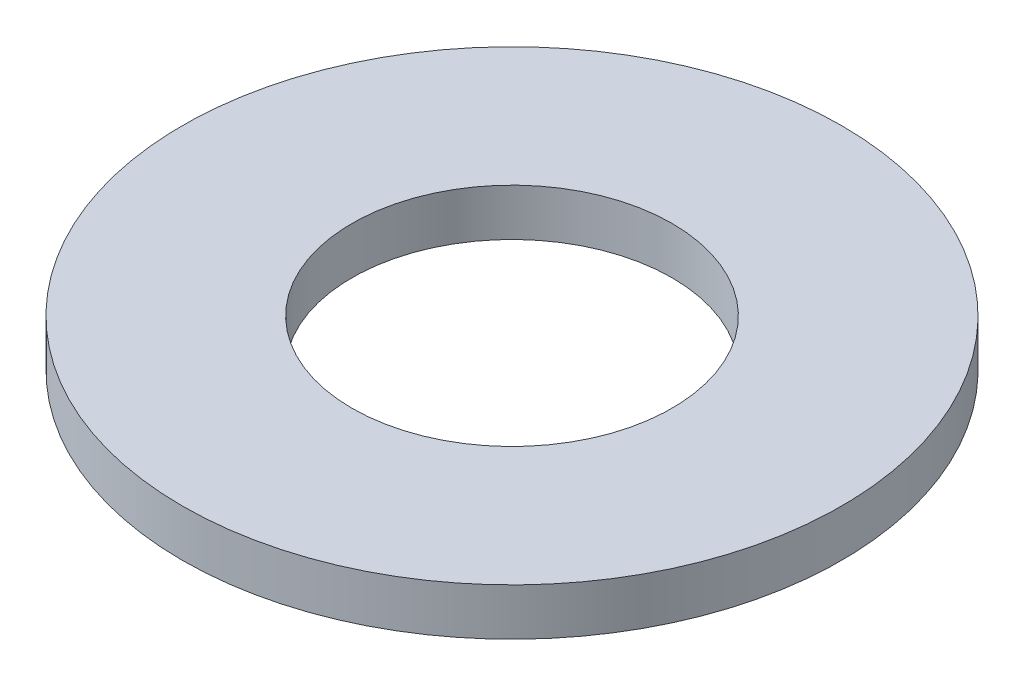
SolidWorks part; units mm, degrees
ref_plane "基准面1" through (0, 0, 0) normal (0, 0, 1) x (1, 0, 0)
ref_plane "基准面2" through (0, 0, 0) normal (0, 1, 0) x (1, 0, 0)
ref_plane "基准面3" through (0, 0, 0) normal (1, 0, 0) x (0, 0, -1)
sketch "尺寸草图" plane through (0, 0, 0) normal (0, 0, 1) x (1, 0, 0)
  line L0 (0, 0) -> (7, 0) construction
  point P3 (0.5, 0)
  point P4 (7, 0)
  point P5 (3.4, 0)
  dimension "h" = 0.5
  dimension "d2" = 7
  dimension "d1" = 3.4
sketch "草图1" plane through (0, 0, 0) normal (0, 0, 1) x (1, 0, 0)
  line L0 (0, 0) -> (0, 52.7318) construction
  line L2 (-1.7, 8.6445) -> (-3.5, 8.6445)
  line L3 (-1.7, 8.6445) -> (-1.7, 9.1445)
  line L4 (-1.7, 9.1445) -> (-3.5, 9.1445)
  line L5 (-3.5, 8.6445) -> (-3.5, 9.1445)
  dimension "D1" = 1.7
  dimension "D2" = 3.5
  dimension "h" = 0.5
revolve "基体-旋转" add sketch "草图1" angle 360 about L0
